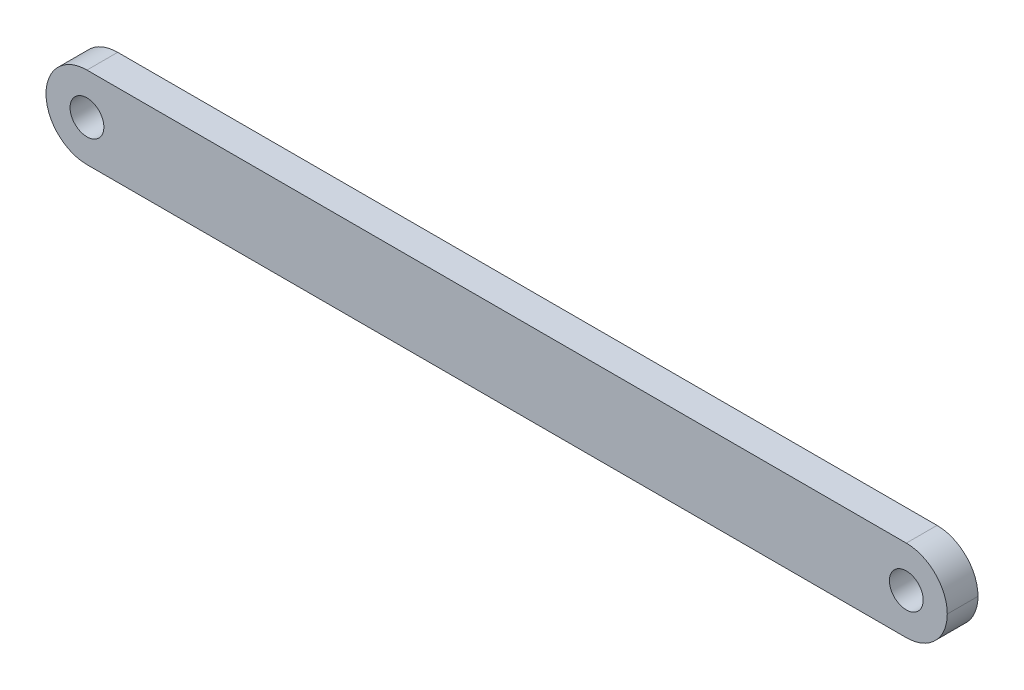
SolidWorks part; units mm, degrees
ref_plane "前视基准面" through (0, 0, 0) normal (0, 0, 1) x (1, 0, 0)
ref_plane "上视基准面" through (0, 0, 0) normal (0, 1, 0) x (1, 0, 0)
ref_plane "右视基准面" through (0, 0, 0) normal (1, 0, 0) x (0, 0, -1)
ref_plane "基准面4" through (0, 0, 0) normal (0, 0, -1) x (-1, 0, 0)
sketch "草图1" plane through (0, 0, 0) normal (0, 0, -1) x (-1, 0, 0)
  line L0 (-55.8602, 0) -> (24.1383, 0)
  line L1 (24.1383, 7.999) -> (-55.8602, 7.999)
  arc A0 (-55.8602, 7.999) -> (-59.8602, 4) centre (-55.8602, 3.999) ccw
  arc A1 (-59.8602, 4) -> (-55.8602, 0) centre (-55.8602, 4) ccw
  arc A2 (24.1383, 0) -> (28.1383, 3.999) centre (24.1383, 4) ccw
  arc A3 (28.1383, 3.999) -> (24.1383, 7.999) centre (24.1383, 3.999) ccw
  circle A4 centre (24.1388, 3.9985) radius 1.3
  circle A5 centre (-55.8597, 3.9995) radius 1.65
extrude "凸台-拉伸1" add sketch "草图1" against normal blind 3
sketch "草图2" plane through (0, 0, 3) normal (0, 0, 1) x (1, 0, 0)
  circle A0 centre (-24.1388, 3.9985) radius 1.65
  dimension "D1" = 3.3
extrude "切除-拉伸1" cut sketch "草图2" against normal through all
sketch "草图3" plane through (0, 0, 0) normal (0, 0, -1) x (-1, 0, 0)
  text T0 "6"
extrude "切除-拉伸2" cut sketch "草图3" against normal blind 1
